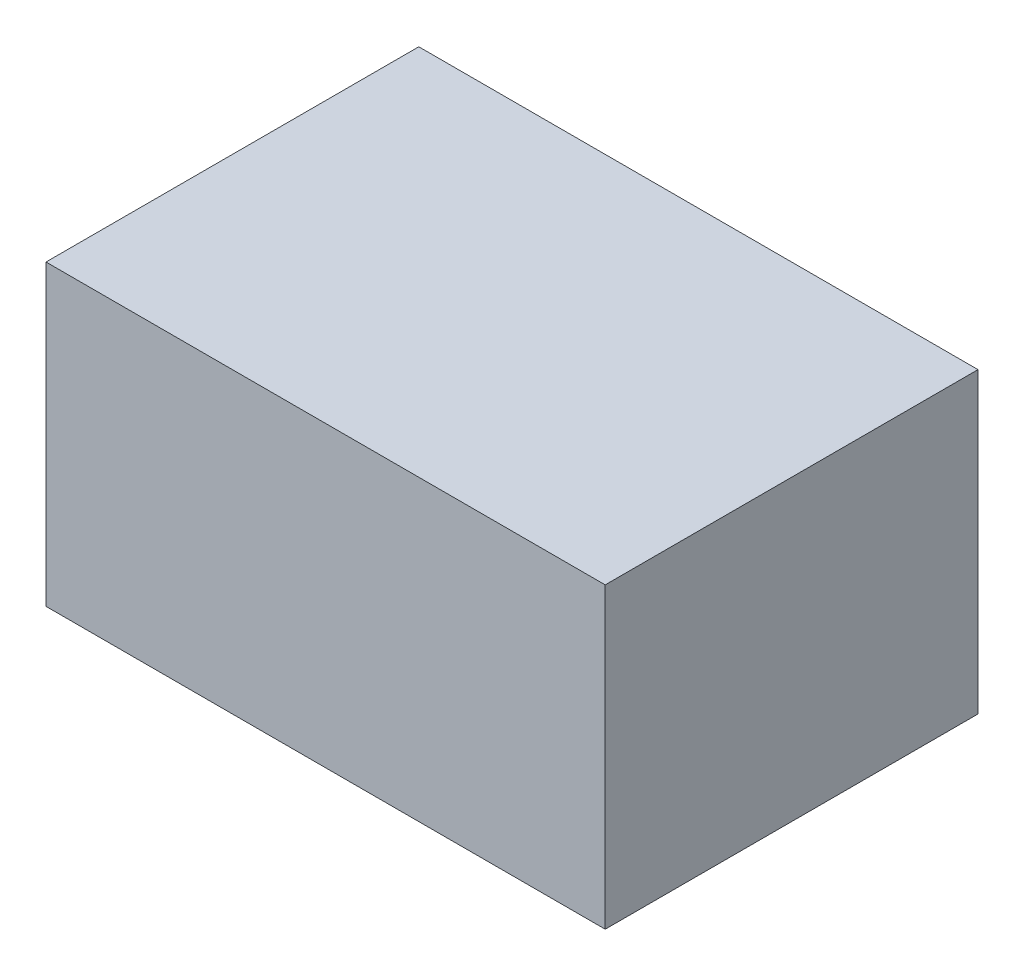
SolidWorks part; units mm, degrees
ref_plane "Front Plane" through (0, 0, 0) normal (0, 0, 1) x (1, 0, 0)
ref_plane "Top Plane" through (0, 0, 0) normal (0, 1, 0) x (1, 0, 0)
ref_plane "Right Plane" through (0, 0, 0) normal (1, 0, 0) x (0, 0, -1)
sketch "Sketch1" plane through (0, 0, 0) normal (0, 0, 1) x (1, 0, 0)
  line L1 (-30, 16) -> (30, 16)
  line L2 (-30, 16) -> (-30, -16)
  line L3 (-30, -16) -> (30, -16)
  line L4 (30, 16) -> (30, -16)
  line L5 (-30, 16) -> (30, -16) construction
  line L6 (-30, -16) -> (30, 16) construction
  point P0 (0, 0)
  dimension "D1" = 60
  dimension "D2" = 32
extrude "Boss-Extrude1" add sketch "Sketch1" against normal blind 40
